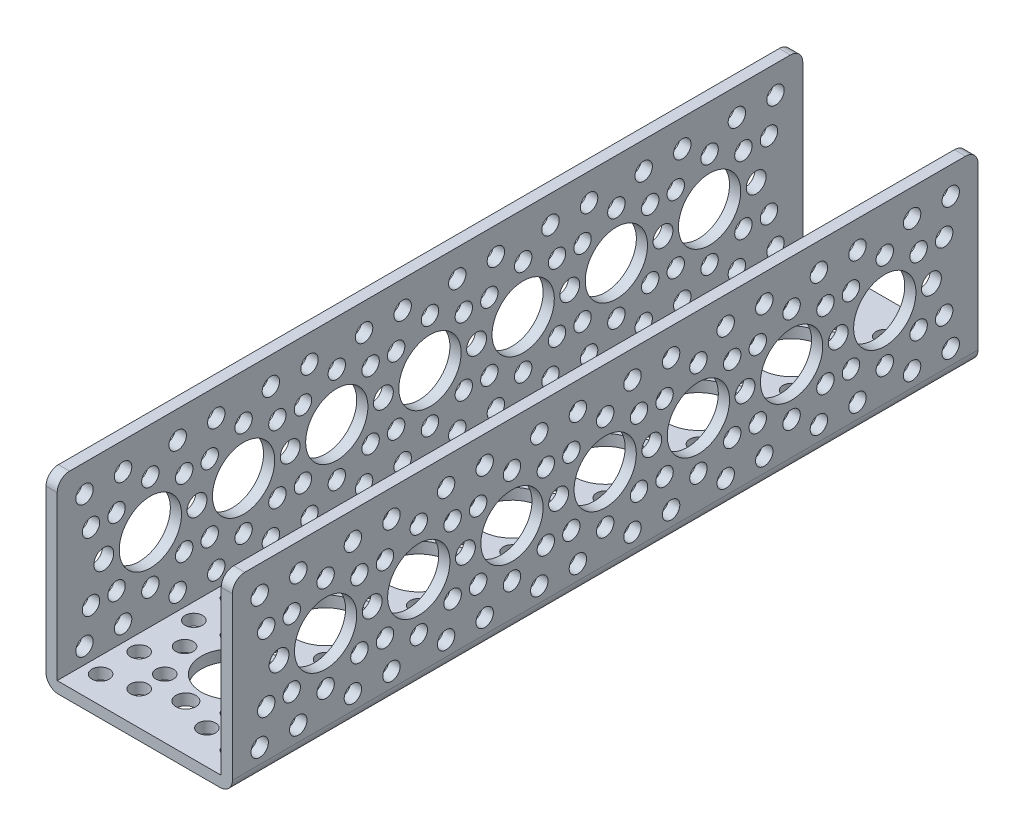
SolidWorks part; units mm, degrees
ref_plane "Front Plane" through (0, 0, 0) normal (0, 0, 1) x (1, 0, 0)
ref_plane "Top Plane" through (0, 0, 0) normal (0, 1, 0) x (1, 0, 0)
ref_plane "Right Plane" through (0, 0, 0) normal (1, 0, 0) x (0, 0, -1)
ref_plane "Plane1" through (0, 0, 0) normal (0, -1, 0) x (1, 0, 0)
sketch "Sketch1" plane through (0, 0, 0) normal (0, -1, 0) x (1, 0, 0)
  line L0 (38.1, 152.4) -> (0, 152.4)
  line L1 (0, 152.4) -> (0, 0)
  line L2 (0, 0) -> (38.1, 0)
  line L3 (38.1, 0) -> (38.1, 152.4)
extrude "Boss-Extrude1" add sketch "Sketch1" against normal blind 38.1
sketch "Sketch2" plane through (0, 0, 152.4) normal (0, 0, 1) x (1, 0, 0)
  line L0 (35.814, 38.1) -> (2.286, 38.1)
  line L1 (2.286, 38.1) -> (2.286, 2.286)
  line L2 (2.286, 2.286) -> (35.814, 2.286)
  line L3 (35.814, 2.286) -> (35.814, 38.1)
extrude "Cut-Extrude1" cut sketch "Sketch2" against normal through all
hole_wizard "Hole1" positions "Sketch4" profile "Sketch3" legacy
sketch "Sketch4" plane through (38.1, 0, 0) normal (1, 0, 0) x (0, 0, -1)
  point P0 (-38.1, 19.05)
  point P1 (-19.05, 19.05)
  point P2 (-57.15, 19.05)
  point P3 (-76.2, 19.05)
  point P4 (-95.25, 19.05)
  point P5 (-114.3, 19.05)
  point P6 (-133.35, 19.05)
sketch "Sketch3" plane through (38.1, 19.05, 38.1) normal (0, 1, 0) x (0, 0, -1)
  line L0 (0, 0) -> (0, 2.286)
  line L1 (0, 2.286) -> (6.3627, 2.286)
  line L2 (6.3627, 2.286) -> (6.3627, 0)
  line L3 (6.3627, 0) -> (0, 0)
  line L4 (0, 110) -> (0, -10) construction
  dimension "Diameter" = 12.7254
  dimension "Depth" = 2.286
hole_wizard "M3 Clearance Hole1" positions "Sketch6" profile "Sketch5" hole size "M3" standard "ANSI Metric"
sketch "Sketch6" plane through (38.1, 0, 0) normal (1, 0, 0) x (0, 0, -1)
  point P0 (-138.9296, 5.5796)
  point P1 (-145.4852, 12.1352)
  point P2 (-138.9296, 32.5204)
  point P3 (-145.4852, 25.9648)
  point P4 (-13.4704, 5.5796)
  point P5 (-6.9148, 12.1352)
  point P6 (-13.4704, 32.5204)
  point P7 (-6.9148, 25.9648)
  point P8 (-119.8796, 5.5796)
  point P9 (-100.8296, 5.5796)
  point P10 (-81.7796, 5.5796)
  point P11 (-62.7296, 5.5796)
  point P12 (-43.6796, 5.5796)
  point P13 (-24.6296, 5.5796)
  point P14 (-119.8796, 32.5204)
  point P15 (-100.8296, 32.5204)
  point P16 (-81.7796, 32.5204)
  point P17 (-62.7296, 32.5204)
  point P18 (-43.6796, 32.5204)
  point P19 (-24.6296, 32.5204)
  point P20 (-146.8204, 5.5796)
  point P21 (-146.8204, 32.5204)
  point P22 (-127.7704, 5.5796)
  point P23 (-127.7704, 32.5204)
  point P24 (-108.7204, 5.5796)
  point P25 (-108.7204, 32.5204)
  point P26 (-89.6704, 5.5796)
  point P27 (-89.6704, 32.5204)
  point P28 (-70.6204, 5.5796)
  point P29 (-70.6204, 32.5204)
  point P30 (-51.5704, 5.5796)
  point P31 (-51.5704, 32.5204)
  point P32 (-126.4352, 12.1352)
  point P33 (-133.35, 9.271)
  point P34 (-140.2648, 12.1352)
  point P35 (-140.2648, 25.9648)
  point P36 (-133.35, 28.829)
  point P37 (-107.3852, 12.1352)
  point P38 (-114.3, 9.271)
  point P39 (-121.2148, 12.1352)
  point P40 (-121.2148, 25.9648)
  point P41 (-114.3, 28.829)
  point P42 (-88.3352, 12.1352)
  point P43 (-95.25, 9.271)
  point P44 (-102.1648, 12.1352)
  point P45 (-102.1648, 25.9648)
  point P46 (-95.25, 28.829)
  point P47 (-69.2852, 12.1352)
  point P48 (-76.2, 9.271)
  point P49 (-83.1148, 12.1352)
  point P50 (-83.1148, 25.9648)
  point P51 (-76.2, 28.829)
  point P52 (-50.2352, 12.1352)
  point P53 (-57.15, 9.271)
  point P54 (-64.0648, 12.1352)
  point P55 (-64.0648, 25.9648)
  point P56 (-57.15, 28.829)
  point P57 (-31.1852, 12.1352)
  point P58 (-38.1, 9.271)
  point P59 (-45.0148, 12.1352)
  point P60 (-45.0148, 25.9648)
  point P61 (-38.1, 28.829)
  point P62 (-126.4352, 25.9648)
  point P63 (-107.3852, 25.9648)
  point P64 (-88.3352, 25.9648)
  point P65 (-69.2852, 25.9648)
  point P66 (-50.2352, 25.9648)
  point P67 (-31.1852, 25.9648)
  point P68 (-32.5204, 5.5796)
  point P69 (-32.5204, 32.5204)
  point P70 (-5.5796, 5.5796)
  point P71 (-5.5796, 32.5204)
  point P72 (-12.1352, 12.1352)
  point P73 (-19.05, 9.271)
  point P74 (-25.9648, 12.1352)
  point P75 (-25.9648, 25.9648)
  point P76 (-19.05, 28.829)
  point P77 (-12.1352, 25.9648)
sketch "Sketch5" plane through (38.1, 5.5796, 138.9296) normal (0, 1, 0) x (0, 0, -1)
  line L0 (0, 0) -> (0, 2.286)
  line L1 (0, 2.286) -> (1.778, 2.286)
  line L2 (1.778, 2.286) -> (1.778, 0)
  line L5 (1.778, 0) -> (0, 0)
  line L11 (0, -6.35) -> (0, 107.95) construction
  dimension "Thru Hole Dia." = 3.556
  dimension "Thru Hole Depth" = 2.286
hole_wizard "M3.5 Clearance Hole1" positions "Sketch8" profile "Sketch7" hole size "M3.5" standard "ANSI Metric"
sketch "Sketch8" plane through (38.1, 0, 0) normal (1, 0, 0) x (0, 0, -1)
  point P0 (-142.875, 19.05)
  point P1 (-123.825, 19.05)
  point P2 (-104.775, 19.05)
  point P3 (-85.725, 19.05)
  point P4 (-66.675, 19.05)
  point P5 (-47.625, 19.05)
  point P6 (-28.575, 19.05)
  point P7 (-9.525, 19.05)
sketch "Sketch7" plane through (38.1, 19.05, 142.875) normal (0, 1, 0) x (0, 0, -1)
  line L0 (0, 0) -> (0, 2.286)
  line L1 (0, 2.286) -> (2.032, 2.286)
  line L2 (2.032, 2.286) -> (2.032, 0)
  line L5 (2.032, 0) -> (0, 0)
  line L11 (0, -6.35) -> (0, 107.95) construction
  dimension "Thru Hole Dia." = 4.064
  dimension "Thru Hole Depth" = 2.286
hole_wizard "Hole2" positions "Sketch10" profile "Sketch9" legacy
sketch "Sketch10" plane through (0, 0, 0) normal (0, -1, 0) x (-1, 0, 0)
  point P0 (-19.05, -133.35)
  point P1 (-19.05, -114.3)
  point P2 (-19.05, -95.25)
  point P3 (-19.05, -76.2)
  point P4 (-19.05, -57.15)
  point P5 (-19.05, -38.1)
  point P6 (-19.05, -19.05)
sketch "Sketch9" plane through (19.05, 0, 133.35) normal (1, 0, 0) x (0, 0, -1)
  line L0 (0, 0) -> (0, 38.1)
  line L1 (0, 38.1) -> (6.3627, 38.1)
  line L2 (6.3627, 38.1) -> (6.3627, 0)
  line L3 (6.3627, 0) -> (0, 0)
  line L4 (0, 110) -> (0, -10) construction
  dimension "Diameter" = 12.7254
  dimension "Depth" = 38.1
hole_wizard "M3.5 Clearance Hole2" positions "Sketch12" profile "Sketch11" hole size "M3.5" standard "ANSI Metric"
sketch "Sketch12" plane through (0, 0, 0) normal (0, -1, 0) x (-1, 0, 0)
  point P0 (-19.05, -142.875)
  point P1 (-19.05, -123.825)
  point P2 (-19.05, -104.775)
  point P3 (-19.05, -85.725)
  point P4 (-19.05, -66.675)
  point P5 (-19.05, -47.625)
  point P6 (-19.05, -28.575)
  point P7 (-19.05, -9.525)
sketch "Sketch11" plane through (19.05, 0, 142.875) normal (1, 0, 0) x (0, 0, -1)
  line L0 (0, 0) -> (0, 38.1)
  line L1 (0, 38.1) -> (2.032, 38.1)
  line L2 (2.032, 38.1) -> (2.032, 0)
  line L5 (2.032, 0) -> (0, 0)
  line L11 (0, -6.35) -> (0, 107.95) construction
  dimension "Thru Hole Dia." = 4.064
  dimension "Thru Hole Depth" = 38.1
hole_wizard "M3 Clearance Hole2" positions "Sketch14" profile "Sketch13" hole size "M3" standard "ANSI Metric"
sketch "Sketch14" plane through (0, 0, 0) normal (0, -1, 0) x (-1, 0, 0)
  point P0 (-5.5796, -146.8204)
  point P1 (-5.5796, -138.9296)
  point P2 (-12.1352, -145.4852)
  point P3 (-32.5204, -146.8204)
  point P4 (-32.5204, -138.9296)
  point P5 (-25.9648, -145.4852)
  point P6 (-5.5796, -127.7704)
  point P7 (-5.5796, -119.8796)
  point P8 (-32.5204, -127.7704)
  point P9 (-32.5204, -119.8796)
  point P10 (-5.5796, -108.7204)
  point P11 (-5.5796, -100.8296)
  point P12 (-32.5204, -108.7204)
  point P13 (-32.5204, -100.8296)
  point P14 (-5.5796, -89.6704)
  point P15 (-5.5796, -81.7796)
  point P16 (-32.5204, -89.6704)
  point P17 (-32.5204, -81.7796)
  point P18 (-5.5796, -70.6204)
  point P19 (-5.5796, -62.7296)
  point P20 (-32.5204, -70.6204)
  point P21 (-32.5204, -62.7296)
  point P22 (-5.5796, -51.5704)
  point P23 (-5.5796, -43.6796)
  point P24 (-32.5204, -51.5704)
  point P25 (-32.5204, -43.6796)
  point P26 (-12.1352, -126.4352)
  point P27 (-9.271, -133.35)
  point P28 (-12.1352, -140.2648)
  point P29 (-25.9648, -140.2648)
  point P30 (-28.829, -133.35)
  point P31 (-25.9648, -126.4352)
  point P32 (-12.1352, -107.3852)
  point P33 (-9.271, -114.3)
  point P34 (-12.1352, -121.2148)
  point P35 (-25.9648, -121.2148)
  point P36 (-28.829, -114.3)
  point P37 (-25.9648, -107.3852)
  point P38 (-12.1352, -88.3352)
  point P39 (-9.271, -95.25)
  point P40 (-12.1352, -102.1648)
  point P41 (-25.9648, -102.1648)
  point P42 (-28.829, -95.25)
  point P43 (-25.9648, -88.3352)
  point P44 (-12.1352, -69.2852)
  point P45 (-9.271, -76.2)
  point P46 (-12.1352, -83.1148)
  point P47 (-25.9648, -83.1148)
  point P48 (-28.829, -76.2)
  point P49 (-25.9648, -69.2852)
  point P50 (-12.1352, -50.2352)
  point P51 (-9.271, -57.15)
  point P52 (-12.1352, -64.0648)
  point P53 (-25.9648, -64.0648)
  point P54 (-28.829, -57.15)
  point P55 (-25.9648, -50.2352)
  point P56 (-9.271, -38.1)
  point P57 (-12.1352, -45.0148)
  point P58 (-25.9648, -45.0148)
  point P59 (-28.829, -38.1)
  point P60 (-5.5796, -32.5204)
  point P61 (-5.5796, -24.6296)
  point P62 (-12.1352, -31.1852)
  point P63 (-32.5204, -32.5204)
  point P64 (-32.5204, -24.6296)
  point P65 (-25.9648, -31.1852)
  point P66 (-5.5796, -5.5796)
  point P67 (-5.5796, -13.4704)
  point P68 (-12.1352, -6.9148)
  point P69 (-32.5204, -5.5796)
  point P70 (-32.5204, -13.4704)
  point P71 (-25.9648, -6.9148)
  point P72 (-12.1352, -12.1352)
  point P73 (-9.271, -19.05)
  point P74 (-12.1352, -25.9648)
  point P75 (-25.9648, -25.9648)
  point P76 (-28.829, -19.05)
  point P77 (-25.9648, -12.1352)
sketch "Sketch13" plane through (5.5796, 0, 146.8204) normal (1, 0, 0) x (0, 0, -1)
  line L0 (0, 0) -> (0, 38.1)
  line L1 (0, 38.1) -> (1.778, 38.1)
  line L2 (1.778, 38.1) -> (1.778, 0)
  line L5 (1.778, 0) -> (0, 0)
  line L11 (0, -6.35) -> (0, 107.95) construction
  dimension "Thru Hole Dia." = 3.556
  dimension "Thru Hole Depth" = 38.1
hole_wizard "Hole3" positions "Sketch16" profile "Sketch15" legacy
sketch "Sketch16" plane through (0, 0, 0) normal (-1, 0, 0) x (0, 0, 1)
  point P0 (38.1, 19.05)
  point P1 (19.05, 19.05)
  point P2 (57.15, 19.05)
  point P3 (76.2, 19.05)
  point P4 (95.25, 19.05)
  point P5 (114.3, 19.05)
  point P6 (133.35, 19.05)
sketch "Sketch15" plane through (0, 19.05, 38.1) normal (0, 1, 0) x (0, 0, 1)
  line L0 (0, 0) -> (0, 38.1)
  line L1 (0, 38.1) -> (6.3627, 38.1)
  line L2 (6.3627, 38.1) -> (6.3627, 0)
  line L3 (6.3627, 0) -> (0, 0)
  line L4 (0, 110) -> (0, -10) construction
  dimension "Diameter" = 12.7254
  dimension "Depth" = 38.1
hole_wizard "M3 Clearance Hole3" positions "Sketch18" profile "Sketch17" hole size "M3" standard "ANSI Metric"
sketch "Sketch18" plane through (0, 0, 0) normal (-1, 0, 0) x (0, 0, 1)
  point P0 (138.9296, 5.5796)
  point P1 (145.4852, 12.1352)
  point P2 (138.9296, 32.5204)
  point P3 (145.4852, 25.9648)
  point P4 (13.4704, 5.5796)
  point P5 (6.9148, 12.1352)
  point P6 (13.4704, 32.5204)
  point P7 (6.9148, 25.9648)
  point P8 (119.8796, 5.5796)
  point P9 (100.8296, 5.5796)
  point P10 (81.7796, 5.5796)
  point P11 (62.7296, 5.5796)
  point P12 (43.6796, 5.5796)
  point P13 (24.6296, 5.5796)
  point P14 (119.8796, 32.5204)
  point P15 (100.8296, 32.5204)
  point P16 (81.7796, 32.5204)
  point P17 (62.7296, 32.5204)
  point P18 (43.6796, 32.5204)
  point P19 (24.6296, 32.5204)
  point P20 (146.8204, 5.5796)
  point P21 (146.8204, 32.5204)
  point P22 (127.7704, 5.5796)
  point P23 (127.7704, 32.5204)
  point P24 (108.7204, 5.5796)
  point P25 (108.7204, 32.5204)
  point P26 (89.6704, 5.5796)
  point P27 (89.6704, 32.5204)
  point P28 (70.6204, 5.5796)
  point P29 (70.6204, 32.5204)
  point P30 (51.5704, 5.5796)
  point P31 (51.5704, 32.5204)
  point P32 (126.4352, 12.1352)
  point P33 (133.35, 9.271)
  point P34 (140.2648, 12.1352)
  point P35 (140.2648, 25.9648)
  point P36 (133.35, 28.829)
  point P37 (107.3852, 12.1352)
  point P38 (114.3, 9.271)
  point P39 (121.2148, 12.1352)
  point P40 (121.2148, 25.9648)
  point P41 (114.3, 28.829)
  point P42 (88.3352, 12.1352)
  point P43 (95.25, 9.271)
  point P44 (102.1648, 12.1352)
  point P45 (102.1648, 25.9648)
  point P46 (95.25, 28.829)
  point P47 (69.2852, 12.1352)
  point P48 (76.2, 9.271)
  point P49 (83.1148, 12.1352)
  point P50 (83.1148, 25.9648)
  point P51 (76.2, 28.829)
  point P52 (50.2352, 12.1352)
  point P53 (57.15, 9.271)
  point P54 (64.0648, 12.1352)
  point P55 (64.0648, 25.9648)
  point P56 (57.15, 28.829)
  point P57 (31.1852, 12.1352)
  point P58 (38.1, 9.271)
  point P59 (45.0148, 12.1352)
  point P60 (45.0148, 25.9648)
  point P61 (38.1, 28.829)
  point P62 (126.4352, 25.9648)
  point P63 (107.3852, 25.9648)
  point P64 (88.3352, 25.9648)
  point P65 (69.2852, 25.9648)
  point P66 (50.2352, 25.9648)
  point P67 (31.1852, 25.9648)
  point P68 (32.5204, 5.5796)
  point P69 (32.5204, 32.5204)
  point P70 (5.5796, 5.5796)
  point P71 (5.5796, 32.5204)
  point P72 (12.1352, 12.1352)
  point P73 (19.05, 9.271)
  point P74 (25.9648, 12.1352)
  point P75 (25.9648, 25.9648)
  point P76 (19.05, 28.829)
  point P77 (12.1352, 25.9648)
sketch "Sketch17" plane through (0, 5.5796, 138.9296) normal (0, 1, 0) x (0, 0, 1)
  line L0 (0, 0) -> (0, 38.1)
  line L1 (0, 38.1) -> (1.778, 38.1)
  line L2 (1.778, 38.1) -> (1.778, 0)
  line L5 (1.778, 0) -> (0, 0)
  line L11 (0, -6.35) -> (0, 107.95) construction
  dimension "Thru Hole Dia." = 3.556
  dimension "Thru Hole Depth" = 38.1
hole_wizard "M3.5 Clearance Hole3" positions "Sketch20" profile "Sketch19" hole size "M3.5" standard "ANSI Metric"
sketch "Sketch20" plane through (0, 0, 0) normal (-1, 0, 0) x (0, 0, 1)
  point P0 (142.875, 19.05)
  point P1 (123.825, 19.05)
  point P2 (104.775, 19.05)
  point P3 (85.725, 19.05)
  point P4 (66.675, 19.05)
  point P5 (47.625, 19.05)
  point P6 (28.575, 19.05)
  point P7 (9.525, 19.05)
sketch "Sketch19" plane through (0, 19.05, 142.875) normal (0, 1, 0) x (0, 0, 1)
  line L0 (0, 0) -> (0, 38.1)
  line L1 (0, 38.1) -> (2.032, 38.1)
  line L2 (2.032, 38.1) -> (2.032, 0)
  line L5 (2.032, 0) -> (0, 0)
  line L11 (0, -6.35) -> (0, 107.95) construction
  dimension "Thru Hole Dia." = 4.064
  dimension "Thru Hole Depth" = 38.1
fillet "Fillet1" radius 2.54 6 edges at (1.143, 38.1, 152.4) (36.957, 38.1, 152.4) (36.957, 38.1, 0) (38.1, 0, 76.2) (1.143, 38.1, 0) (0, 0, 76.2)
